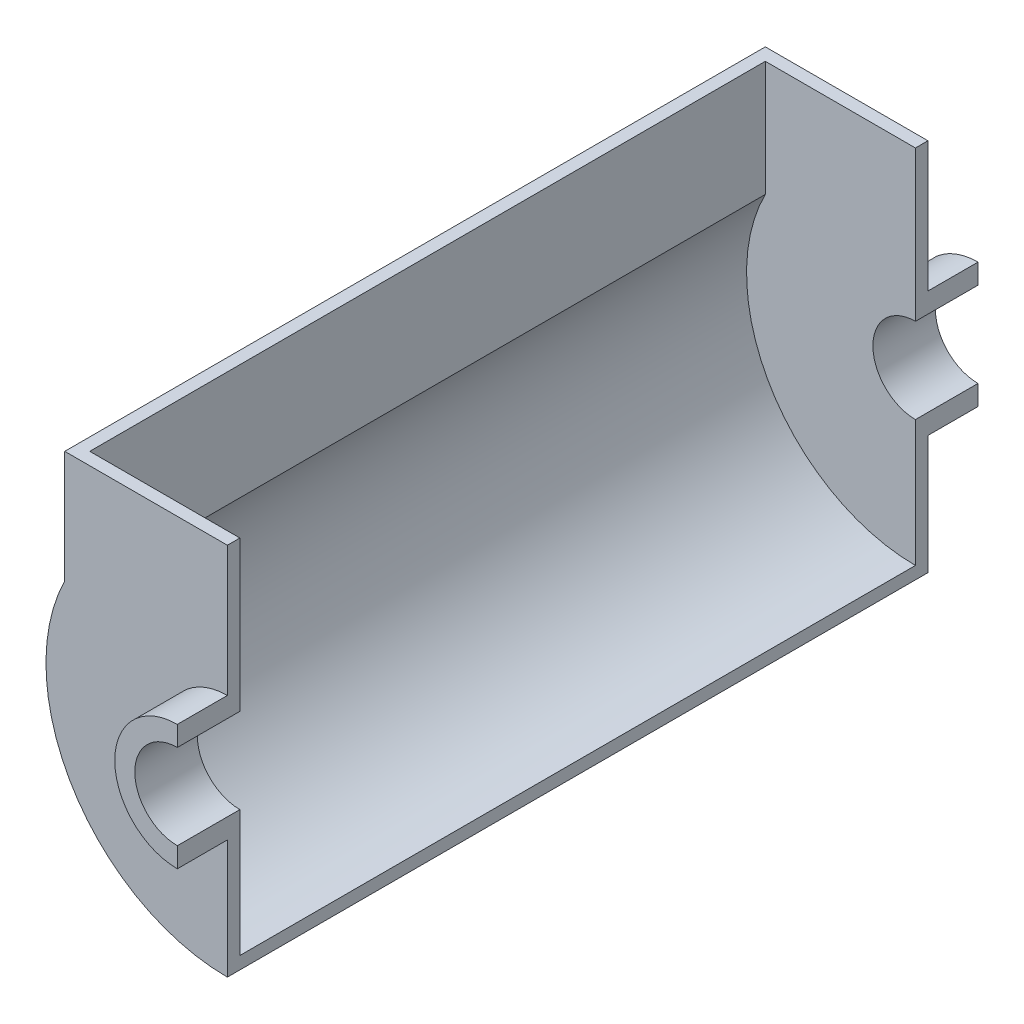
SolidWorks part; units mm, degrees
ref_plane "Front Plane" through (0, 0, 0) normal (0, 0, 1) x (1, 0, 0)
ref_plane "Top Plane" through (0, 0, 0) normal (0, 1, 0) x (1, 0, 0)
ref_plane "Right Plane" through (0, 0, 0) normal (1, 0, 0) x (0, 0, -1)
sketch "Sketch1" plane through (0, 0, 0) normal (0, 0, 1) x (1, 0, 0)
  line L0 (0, 25) -> (0, 17)
  line L1 (0, -17) -> (0, -25)
  arc A0 (0, 17) -> (0, -17) centre (0, 0) ccw
  arc A1 (0, 25) -> (0, -25) centre (0, 0) ccw
  dimension "D1" = 50
  dimension "D2" = 34
extrude "Boss-Extrude1" add sketch "Sketch1" along normal blind 20 and the other way blind 5
sketch "Sketch2" plane through (0, 0, 0) normal (0, 0, 1) x (1, 0, 0)
  line L0 (0, 25) -> (0, 77)
  line L1 (0, 77) -> (-65, 77)
  line L2 (-65, 77) -> (-65, 32.1131)
  line L3 (0, -25) -> (0, -72.5)
  arc A0 (0, 25) -> (0, -25) centre (0, 0) ccw construction
  arc A1 (0, 25) -> (0, -25) centre (0, 0) ccw
  arc A2 (-65, 32.1131) -> (0, -72.5) centre (0, 0) ccw
  dimension "D3" = 72.5
  dimension "D1" = 52
  dimension "D2" = 65
extrude "Boss-Extrude2" add sketch "Sketch2" against normal blind 5
ref_plane "Plane1" through (0, 0, -140) normal (0, 0, 1) x (1, 0, 0)
sketch "Sketch3" plane through (0, 0, -5) normal (0, 0, -1) x (-1, 0, 0)
  line L0 (60, 30.9233) -> (60, 77)
  line L1 (60, 77) -> (65, 77)
  line L2 (0, -67.5) -> (0, -72.5)
  line L4 (0, -17) -> (0, -72.5)
  line L5 (65, 32.1131) -> (65, 77)
  line L6 (65, 77) -> (0, 77)
  line L7 (0, 77) -> (0, 17)
  line L9 (65, 32.1131) -> (65, 77)
  arc A0 (0, -67.5) -> (60, 30.9233) centre (0, 0) ccw
  arc A2 (0, -17) -> (0, 17) centre (0, 0) ccw
  arc A3 (0, -72.5) -> (65, 32.1131) centre (0, 0) ccw
  arc A5 (0, -72.5) -> (65, 32.1131) centre (0, 0) ccw
  dimension "D1" = 0
  dimension "D2" = 5
extrude "Boss-Extrude3" add sketch "Sketch3" along normal up to surface (135 mm away) up to plane "Plane1"
mirror "Mirror5" about plane through (0, 0, -140) normal (0, 0, 1) of bodies 103
